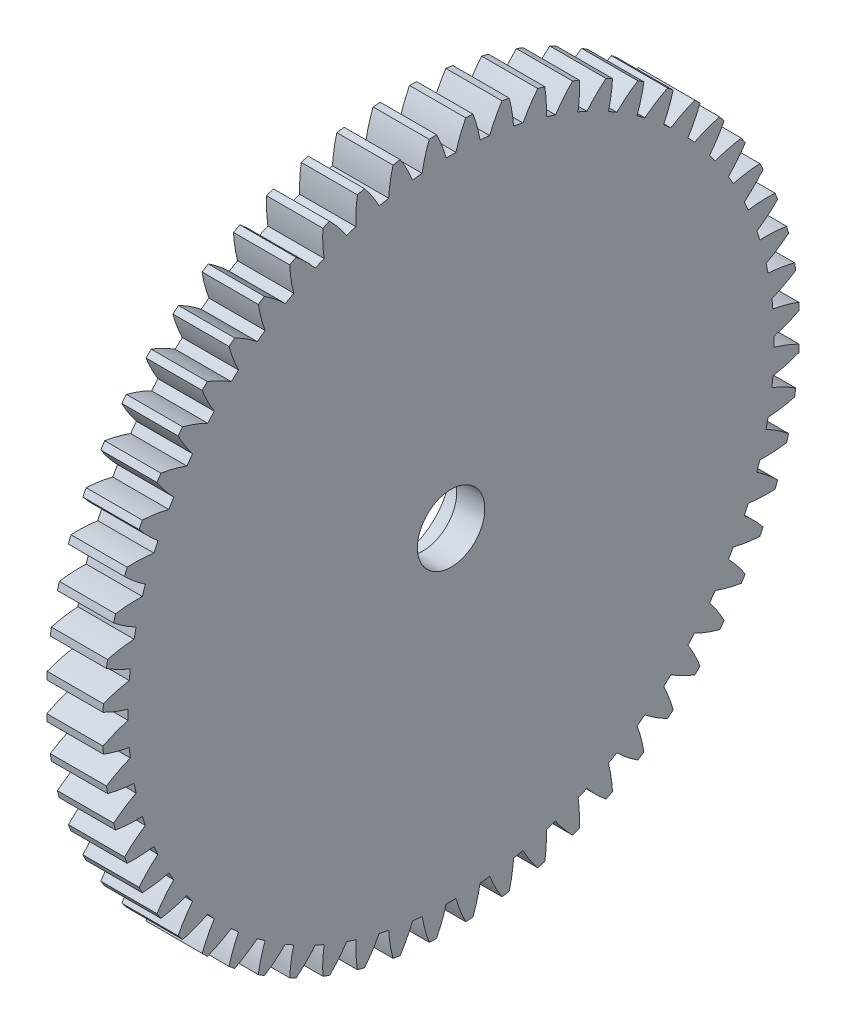
SolidWorks part; units mm, degrees
material "ABS"
ref_plane "Plane1" through (0, 0, 0) normal (0, 0, 1) x (1, 0, 0)
ref_plane "Plane2" through (0, 0, 0) normal (0, 1, 0) x (1, 0, 0)
ref_plane "Plane3" through (0, 0, 0) normal (1, 0, 0) x (0, 0, -1)
sketch "HoldingSke" plane through (0, 0, 0) normal (0, 1, 0) x (1, 0, 0)
  line L0 (0, 0) -> (0.5, -0.866)
  line L1 (-15, 0) -> (100, 0) construction
  line L2 (0, 0) -> (-2.1039, 2.3779)
  line L3 (0, 0) -> (-11.863, 4.5341)
  line L4 (0, 0) -> (4.318, 7.479)
  line L5 (0, 0) -> (-46.8476, -17.4728)
  line L6 (0, 0) -> (-4.1448, -2.7965)
  line L7 (-2.1039, 2.3779) -> (8.6586, 51.2059)
  line L8 (-76.2, 54.61) -> (-75.2, 54.61)
  line L9 (-71.009, 38.7566) -> (-53.1078, 45.2721)
  line L10 (-76.2, 71.12) -> (104.1128, 71.12)
  line L11 (0, 0) -> (-5, 0)
  line L12 (-76.2, 101.6) -> (-76.162, 101.6)
  line L13 (24.9733, 27.94) -> (52.9518, 28.4284)
  line L14 (24.9733, 27.94) -> (24.9743, 27.94)
  line L15 (24.9733, 27.94) -> (100.4006, 29.5858)
  line L16 (-63.627, -1) -> (-12.827, -1)
  circle A0 centre (0, 0) radius 3
  circle A1 centre (0, 0) radius 28.749
  circle A2 centre (0, 0) radius 37.5
  circle A3 centre (0, 0) radius 3
  dimension "MHD" = 57.498
  dimension "Hub_dia" = 75
  dimension "Bore" = 6
  dimension "MBD" = 6
  dimension "Num_teeth" = 60
  dimension "Pitch" = 1
  dimension "Overall_len" = 50
  dimension "Show_teeth" = 60
  dimension "Thickness" = 5
  dimension "OAL" = 50.0001
  dimension "T_dim" = 1
  dimension "Ap" = 20
  dimension "H" = 19.05
  dimension "Pitch_radius" = 180.3128
  dimension "Width" = 5
  dimension "Backlash" = 0.038
  dimension "Addendum_fac" = 1
  dimension "Dedendum_fac" = 1.25
  dimension "Clearance_fac" = 0.25
  dimension "Dedendum_add" = 0.001
  dimension "Module" = 1
sketch "BasProSke" plane through (0, 0, 0) normal (0, 1, 0) x (1, 0, 0)
  line L0 (-10, 0) -> (60, 0) construction
  line L1 (0, 0) -> (0, 31)
  line L2 (0, 0) -> (5, 0)
  line L3 (5, 0) -> (5, 31)
  line L4 (5, 31) -> (0, 31)
  dimension "Thickness" = 5
  dimension "Diameter" = 62
revolve "Base-Revolve" add sketch "BasProSke" angle 360 about L0
sketch "TooCutSke" plane through (0, 0, 0) normal (1, 0, 0) x (0, 0, -1)
  line L1 (0, 0) -> (0, 107) construction
  line L2 (0, 0) -> (-0.8518, 29.9879) construction
  line L3 (0, 0) -> (-3.1393, 59.9006) construction
  line L4 (-0.8518, 29.9879) -> (-1.5696, 29.9503) construction
  arc A0 (0.4302, 28.7458) -> (-0.4302, 28.7458) centre (0, 0) ccw
  arc A1 (1.3127, 30.9976) -> (-1.3127, 30.9976) centre (0, 0) ccw
  circle A2 centre (0, 0) radius 30 construction
  circle A3 centre (0, 0) radius 28.1908 construction
  arc A4 (-0.4302, 28.7458) -> (-1.3127, 30.9976) centre (-11.9871, 25.5153) ccw
  arc A5 (1.3127, 30.9976) -> (0.4302, 28.7458) centre (11.9871, 25.5153) ccw
  dimension "Root_dia" = 57.498
  dimension "Overcut_dia" = 62.0508
  dimension "Pitch_dia" = 60
  dimension "Base_dia" = 56.3816
  dimension "Flank_rad" = 12
  dimension "Half_ang" = 3
  dimension "Half_CT" = 0.7188
extrude "ToothCut" cut sketch "TooCutSke" along normal through all
fillet "Breaks" [suppressed] radius 0.02
fillet "RootFillets" [suppressed] radius 0.251
pattern_circular "TeethCuts" count 60 every 6 about axis through (-10, 0, 0) along (1, 0, 0) of "ToothCut", "RootFillets", "Breaks"
sketch "HubNeaOneSke" plane through (0, 0, 0) normal (-1, 0, 0) x (0, 0, 1)
  circle A0 centre (0, 0) radius 28.749
  dimension "Diameter" = 57.498
extrude "HubNearOne" [suppressed] add sketch "HubNeaOneSke" along normal blind 45.0001
sketch "HubNeaBotSke" plane through (0, 0, 0) normal (-1, 0, 0) x (0, 0, 1)
  circle A0 centre (0, 0) radius 28.749
  dimension "Diameter" = 57.498
extrude "HubNearBoth" [suppressed] add sketch "HubNeaBotSke" along normal blind 22.5
ref_plane "FarPln" through (5, 0, 0) normal (1, 0, 0) x (0, 0, -1)
sketch "HubFarSke" plane through (5, 0, 0) normal (1, 0, 0) x (0, 0, -1)
  circle A0 centre (0, 0) radius 28.749
  dimension "Diameter" = 57.498
extrude "HubFar" [suppressed] add sketch "HubFarSke" along normal blind 22.5
sketch "BorSke" plane through (0, 0, 0) normal (1, 0, 0) x (0, 0, -1)
  circle A0 centre (0, 0) radius 3
  dimension "Diameter" = 6
extrude "Bore" cut sketch "BorSke" along normal mid plane 100.0001
sketch "KeySke" plane through (0, 0, 0) normal (1, 0, 0) x (0, 0, -1)
  line L0 (-1, 0) -> (-1, 4)
  line L1 (-1, 4) -> (1, 4)
  line L2 (1, 4) -> (1, 0)
  line L3 (0, 0) -> (0, 34) construction
  line L4 (-1, 0) -> (1, 0)
  dimension "Offset" = 4
  dimension "Width" = 2
extrude "Keyway" [suppressed] cut sketch "KeySke" along normal mid plane 100.0001
pattern_circular "Keyway2" [suppressed] count 2 every 90 about axis through (-10, 0, 0) along (1, 0, 0)
sketch "Sketch1" plane through (0, 0, 0) normal (-1, 0, 0) x (0, 0, 1)
  circle A0 centre (0, 0) radius 5
  dimension "D1" = 10
extrude "Cut-Extrude1" cut sketch "Sketch1" against normal blind 2.5
equation "' \"Module@HoldingSke\" = 6.35"
equation "' \"Num_teeth@HoldingSke\" = 12"
equation "' \"Ap@HoldingSke\" =  20"
equation "' \"Ap@HoldingSke\" = 20"
equation "' \"Width@HoldingSke\" = 0.5 * 25.4"
equation "' \"Hub_dia@HoldingSke\"= 1 * 25.4"
equation "' \"Hub_dia@HoldingSke\" = 1 * 25.4"
equation "' \"Overall_len@HoldingSke\" = 1.0 * 25.4"
equation "' \"Bore@HoldingSke\" = 0.75 * 25.4"
equation "' \"T_dim@HoldingSke\" = 0.1 * 25.4"
equation "' \"Width@KeySke\" = 0.25 * 25.4"
equation "' \"Show_teeth@HoldingSke\" = 13"
equation "' \"Backlash@HoldingSke\" = 0.009 * 25.4"
equation "' \"Addendum_fac@HoldingSke\" = 1.0"
equation "' \"Dedendum_fac@HoldingSke\" = 1.25"
equation "' \"Dedendum_add@HoldingSke\" = 0.00005 * 25.4"
equation "' \"Clearance_fac@HoldingSke\" = 0.25"
equation "\"Pitch@HoldingSke\" = 1 / \"Module@HoldingSke\""
equation "\"Overcut_dia@TooCutSke\" = (\"Num_teeth@HoldingSke\" + 2 * \"Addendum_fac@HoldingSke\") / \"Pitch@HoldingSke\" + 0.002 * 25.4"
equation "\"Pitch_dia@TooCutSke\" = \"Num_teeth@HoldingSke\" / \"Pitch@HoldingSke\""
equation "\"Base_dia@TooCutSke\" = \"Num_teeth@HoldingSke\" / \"Pitch@HoldingSke\" * cos((\"Ap@HoldingSke\"  * 3.14159265 / 180))"
equation "\"Root_dia@TooCutSke\" = (\"Num_teeth@HoldingSke\" + 2) / \"Pitch@HoldingSke\" - 2 * (\"Addendum_fac@HoldingSke\" + \"Dedendum_fac@HoldingSke\") / \"Pitch@HoldingSke\" - \"Dedendum_add@HoldingSke\" * 2"
equation "\"Half_ang@TooCutSke\" = 180 / \"Num_teeth@HoldingSke\""
equation "\"Half_CT@TooCutSke\" = \"Num_teeth@HoldingSke\" / \"Pitch@HoldingSke\" * sin((3.14159265 / 2 / \"Num_teeth@HoldingSke\")) / 2 - 7 * \"Backlash@HoldingSke\" / 4"
equation "\"Flank_rad@TooCutSke\" = \"Num_teeth@HoldingSke\" / \"Pitch@HoldingSke\" / 5"
equation "\"Radius@RootFillets\" = \"Clearance_fac@HoldingSke\" / \"Pitch@HoldingSke\" + \"Dedendum_add@HoldingSke\""
equation "\"Break_rad@Breaks\" = 0.02 / \"Pitch@HoldingSke\""
equation "\"Thickness@HoldingSke\" = \"Width@HoldingSke\""
equation "\"OAL@HoldingSke\" = \"Thickness@HoldingSke\""
equation "\"MHD@HoldingSke\" = (\"Num_teeth@HoldingSke\" + 2) / \"Pitch@HoldingSke\" - 2 * (\"Addendum_fac@HoldingSke\" + \"Dedendum_fac@HoldingSke\")  / \"Pitch@HoldingSke\" - \"Dedendum_add@HoldingSke\" * 2"
equation "\"MBD@HoldingSke\" = (\"Num_teeth@HoldingSke\" + 2) / \"Pitch@HoldingSke\" - 2 * (\"Addendum_fac@HoldingSke\" + \"Dedendum_fac@HoldingSke\")  / \"Pitch@HoldingSke\" - \"Dedendum_add@HoldingSke\" * 2 - 0.002 * 25.4"
equation "\"MHD@HoldingSke\" = ((sgn( \"MHD@HoldingSke\" - \"Hub_dia@HoldingSke\" )-1)*( \"MHD@HoldingSke\" - \"Hub_dia@HoldingSke\" ))/-2+ \"Hub_dia@HoldingSke\""
equation "\"MBD@HoldingSke\" = ((sgn( \"MBD@HoldingSke\" - \"Bore@HoldingSke\" )-1)*( \"MBD@HoldingSke\" - \"Bore@HoldingSke\" ))/-2+ \"Bore@HoldingSke\""
equation "\"OAL@HoldingSke\" = ((sgn( \"OAL@HoldingSke\" - \"Overall_len@HoldingSke\" )+1)*( \"OAL@HoldingSke\" - \"Overall_len@HoldingSke\" ))/2 + \"Overall_len@HoldingSke\" + 0.000002 * 25.4"
equation "\"Num_teeth@TeethCuts\" = int( \"Show_teeth@HoldingSke\" ) + 1"
equation "\"Num_teeth@TeethCuts\" = ((sgn( \"Num_teeth@TeethCuts\" - \"Num_teeth@HoldingSke\" )-1)*( \"Num_teeth@TeethCuts\" - \"Num_teeth@HoldingSke\" ))/-2+ \"Num_teeth@HoldingSke\""
equation "\"Num_teeth@TeethCuts\" = ((sgn( \"Num_teeth@TeethCuts\" - 2.0)+1)*( \"Num_teeth@TeethCuts\" - 2.0))/2 +2.0"
equation "\"Angle@TeethCuts\" = 360.0 / \"Num_teeth@HoldingSke\""
equation "\"Diameter@BasProSke\" = (\"Num_teeth@HoldingSke\" + 2 * \"Addendum_fac@HoldingSke\") / \"Pitch@HoldingSke\""
equation "\"Thickness@BasProSke\"  = \"Thickness@HoldingSke\""
equation "' \"Fillet_rad@BasProSke\" =  \"Thickness@HoldingSke\" * 0.05"
equation "' \"Fillet_rad@BasProSke\" = \"Thickness@HoldingSke\" * 0.05"
equation "\"MHD@HoldingSke\" = ((sgn( \"MHD@HoldingSke\" - \"Root_dia@TooCutSke\" )-1)*( \"MHD@HoldingSke\" - \"Root_dia@TooCutSke\" ))/-2+ \"Root_dia@TooCutSke\""
equation "\"Diameter@HubNeaOneSke\" = \"MHD@HoldingSke\""
equation "\"Length@HubNearOne\" = \"OAL@HoldingSke\" - \"Thickness@BasProSke\""
equation "\"Diameter@HubNeaBotSke\" = \"MHD@HoldingSke\""
equation "\"Length@HubNearBoth\" = ( \"OAL@HoldingSke\" - \"Thickness@BasProSke\" ) / 2.0"
equation "\"Thickness@FarPln\" = \"Thickness@BasProSke\""
equation "\"Diameter@HubFarSke\" = \"MHD@HoldingSke\""
equation "\"Length@HubFar\" = ( \"OAL@HoldingSke\" - \"Thickness@BasProSke\" ) / 2.0"
equation "\"Diameter@BorSke\" = \"MBD@HoldingSke\""
equation "\"D1@Bore\" = \"OAL@HoldingSke\" * 2.0"
equation "\"D1@Keyway\" = \"OAL@HoldingSke\" * 2.0"
equation "\"Offset@KeySke\" = \"T_dim@HoldingSke\" + \"MBD@HoldingSke\" / 2.0"
